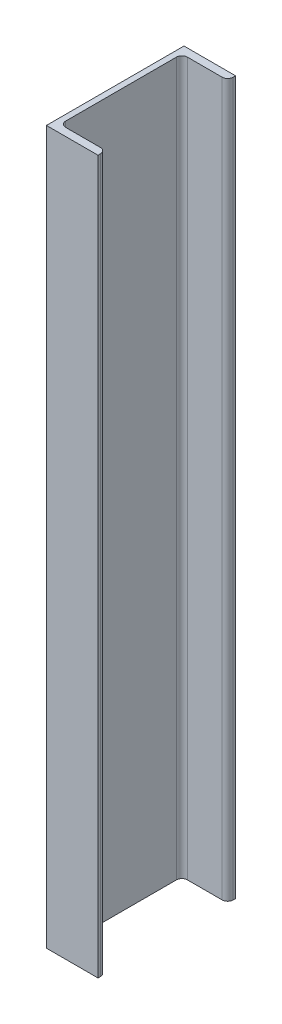
SolidWorks part; units mm, degrees
material "ASTM A36 Steel"
ref_plane "Front Plane" through (0, 0, 0) normal (0, 0, 1) x (1, 0, 0)
ref_plane "Top Plane" through (0, 0, 0) normal (0, 1, 0) x (1, 0, 0)
ref_plane "Right Plane" through (0, 0, 0) normal (1, 0, 0) x (0, 0, -1)
sketch "Sketch1" plane through (0, 0, 0) normal (0, 1, 0) x (1, 0, 0)
  line L0 (-38.4426, 80.9836) -> (-113.4426, 80.9836)
  line L1 (-113.4426, 80.9836) -> (-113.4426, -119.0164)
  line L2 (-113.4426, -119.0164) -> (-38.4426, -119.0164)
  line L3 (-38.4426, -119.0164) -> (-38.4426, -115.5164)
  line L4 (-46.4426, -107.5164) -> (-96.9426, -107.5164)
  line L5 (-104.9426, -99.5164) -> (-104.9426, 61.4836)
  line L6 (-96.9426, 69.4836) -> (-46.4426, 69.4836)
  line L7 (-38.4426, 80.9836) -> (-38.4426, 77.4836)
  arc A0 (-38.4426, -115.5164) -> (-46.4426, -107.5164) centre (-46.4426, -115.5164) ccw
  arc A1 (-96.9426, -107.5164) -> (-104.9426, -99.5164) centre (-96.9426, -99.5164) cw
  arc A2 (-104.9426, 61.4836) -> (-96.9426, 69.4836) centre (-96.9426, 61.4836) cw
  arc A3 (-46.4426, 69.4836) -> (-38.4426, 77.4836) centre (-46.4426, 77.4836) ccw
  dimension "D7" = 8
  dimension "D1" = 200
  dimension "D2" = 75
  dimension "D3" = 75
  dimension "D4" = 8.5
  dimension "D5" = 11.5
  dimension "D6" = 11.5
extrude "Boss-Extrude1" add sketch "Sketch1" along normal blind 1036
